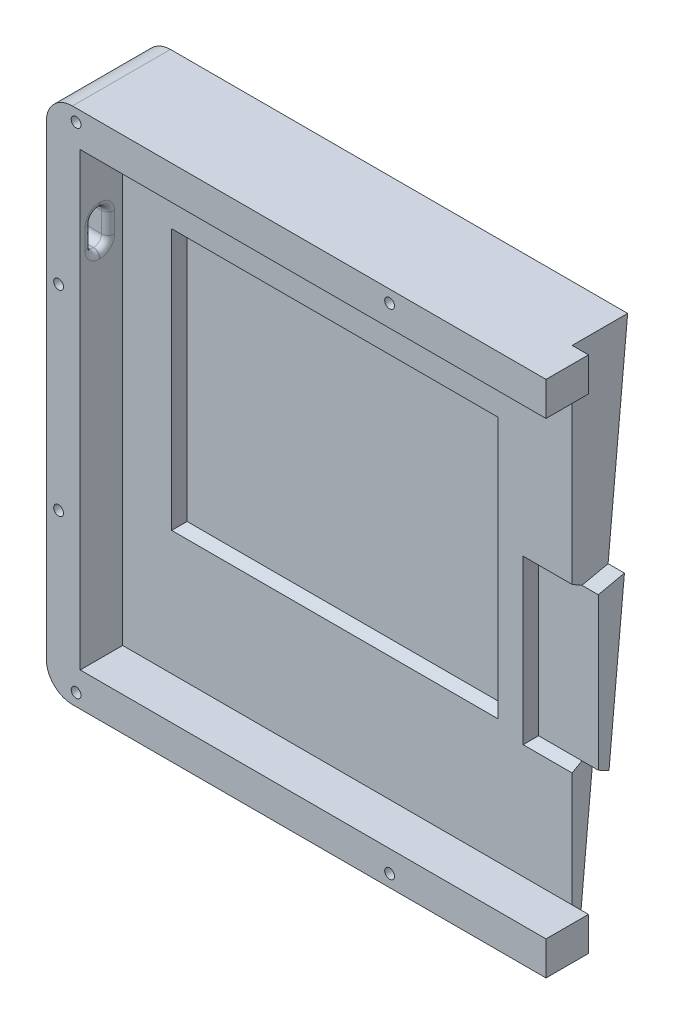
SolidWorks part; units mm, degrees
ref_plane "Front Plane" through (0, 0, 0) normal (0, 0, 1) x (1, 0, 0)
ref_plane "Top Plane" through (0, 0, 0) normal (0, 1, 0) x (1, 0, 0)
ref_plane "Right Plane" through (0, 0, 0) normal (1, 0, 0) x (0, 0, -1)
sketch "Model" plane through (0, 0, 0) normal (0, 0, 1) x (1, 0, 0)
  line L0 (0, 11) -> (0, 150.75)
  line L1 (306.2071, 11.0112) -> (306.0112, 150.7612)
  line L2 (298.0112, 158.75) -> (8, 158.75)
  line L3 (0, 11) -> (0, 8)
  line L4 (8, 0) -> (298.2071, 0)
  line L5 (306.2071, 11.0112) -> (306.2071, 8)
  line L6 (295.63, 10.37) -> (10.37, 10.37)
  line L7 (10.37, 10.37) -> (10.37, 148.38)
  line L8 (10.37, 148.38) -> (295.63, 148.38)
  line L9 (295.63, 148.38) -> (295.63, 10.37)
  arc A0 (8, 158.75) -> (0, 150.75) centre (8, 150.75) ccw
  arc A1 (306.0112, 150.7612) -> (298.0112, 158.75) centre (298.0112, 150.75) ccw
  arc A2 (0, 8) -> (8, 0) centre (8, 8) ccw
  arc A3 (298.2071, 0) -> (306.2071, 8) centre (298.2071, 8) ccw
  circle A4 centre (105.1086, 3.75) radius 1.5
  circle A5 centre (9.1086, 3.75) radius 1.5
  circle A6 centre (201.1085, 3.8173) radius 1.5
  circle A7 centre (297.1084, 3.9518) radius 1.5
  circle A8 centre (105.1086, 155) radius 1.5
  circle A9 centre (9.1086, 155) radius 1.5
  circle A10 centre (201.1085, 154.9327) radius 1.5
  circle A11 centre (297.1084, 154.7982) radius 1.5
  circle A12 centre (3.75, 109.375) radius 1.5
  circle A13 centre (3.75, 49.375) radius 1.5
  circle A14 centre (302.3189, 109.5842) radius 1.5
  circle A15 centre (302.403, 49.5843) radius 1.5
sketch "草图2" plane through (0, 0, 0) normal (0, 0, 1) x (1, 0, 0)
  line L0 (0, 11) -> (0, 150.75)
  line L1 (306.2071, 11.0112) -> (306.0112, 150.7612)
  line L2 (298.0112, 158.75) -> (8, 158.75)
  line L3 (0, 11) -> (0, 8)
  line L4 (8, 0) -> (298.2071, 0)
  line L5 (306.2071, 11.0112) -> (306.2071, 8)
  line L6 (295.63, 10.37) -> (10.37, 10.37)
  line L7 (10.37, 10.37) -> (10.37, 148.38)
  line L8 (10.37, 148.38) -> (295.63, 148.38)
  line L9 (295.63, 148.38) -> (295.63, 10.37)
  arc A0 (8, 158.75) -> (0, 150.75) centre (8, 150.75) ccw
  arc A1 (306.0112, 150.7612) -> (298.0112, 158.75) centre (298.0112, 150.75) ccw
  arc A2 (0, 8) -> (8, 0) centre (8, 8) ccw
  arc A3 (298.2071, 0) -> (306.2071, 8) centre (298.2071, 8) ccw
  circle A4 centre (105.1086, 3.75) radius 1.5
  circle A5 centre (9.1086, 3.75) radius 1.5
  circle A6 centre (201.1085, 3.8173) radius 1.5
  circle A7 centre (297.1084, 3.9518) radius 1.5
  circle A8 centre (105.1086, 155) radius 1.5
  circle A9 centre (9.1086, 155) radius 1.5
  circle A10 centre (201.1085, 154.9327) radius 1.5
  circle A11 centre (297.1084, 154.7982) radius 1.5
  circle A12 centre (3.75, 109.375) radius 1.5
  circle A13 centre (3.75, 49.375) radius 1.5
  circle A14 centre (302.3189, 109.5842) radius 1.5
  circle A15 centre (302.403, 49.5843) radius 1.5
sketch "草图3" plane through (0, 0, 0) normal (0, 0, 1) x (1, 0, 0)
  line L0 (0, 11) -> (0, 150.75)
  line L1 (306.2071, 11.0112) -> (306.0112, 150.7612)
  line L2 (298.0112, 158.75) -> (8, 158.75)
  line L3 (0, 11) -> (0, 8)
  line L4 (8, 0) -> (298.2071, 0)
  line L5 (306.2071, 11.0112) -> (306.2071, 8)
  line L6 (295.63, 10.37) -> (10.37, 10.37)
  line L7 (10.37, 10.37) -> (10.37, 148.38)
  line L8 (10.37, 148.38) -> (295.63, 148.38)
  line L9 (295.63, 148.38) -> (295.63, 10.37)
  arc A0 (8, 158.75) -> (0, 150.75) centre (8, 150.75) ccw
  arc A1 (306.0112, 150.7612) -> (298.0112, 158.75) centre (298.0112, 150.75) ccw
  arc A2 (0, 8) -> (8, 0) centre (8, 8) ccw
  arc A3 (298.2071, 0) -> (306.2071, 8) centre (298.2071, 8) ccw
  circle A4 centre (105.1086, 3.75) radius 1.5
  circle A5 centre (9.1086, 3.75) radius 1.5
  circle A6 centre (201.1085, 3.8173) radius 1.5
  circle A7 centre (297.1084, 3.9518) radius 1.5
  circle A8 centre (105.1086, 155) radius 1.5
  circle A9 centre (9.1086, 155) radius 1.5
  circle A10 centre (201.1085, 154.9327) radius 1.5
  circle A11 centre (297.1084, 154.7982) radius 1.5
  circle A12 centre (3.75, 109.375) radius 1.5
  circle A13 centre (3.75, 49.375) radius 1.5
  circle A14 centre (302.3189, 109.5842) radius 1.5
  circle A15 centre (302.403, 49.5843) radius 1.5
sketch "草图4" plane through (0, 0, 0) normal (0, 0, 1) x (1, 0, 0)
  line L0 (0, 11) -> (0, 150.75)
  line L1 (306.2071, 11.0112) -> (306.0112, 150.7612)
  line L2 (298.0112, 158.75) -> (8, 158.75)
  line L3 (0, 11) -> (0, 8)
  line L4 (8, 0) -> (298.2071, 0)
  line L5 (306.2071, 11.0112) -> (306.2071, 8)
  line L6 (295.63, 10.37) -> (10.37, 10.37)
  line L7 (10.37, 10.37) -> (10.37, 148.38)
  line L8 (10.37, 148.38) -> (295.63, 148.38)
  line L9 (295.63, 148.38) -> (295.63, 10.37)
  arc A0 (8, 158.75) -> (0, 150.75) centre (8, 150.75) ccw
  arc A1 (306.0112, 150.7612) -> (298.0112, 158.75) centre (298.0112, 150.75) ccw
  arc A2 (0, 8) -> (8, 0) centre (8, 8) ccw
  arc A3 (298.2071, 0) -> (306.2071, 8) centre (298.2071, 8) ccw
  circle A4 centre (105.1086, 3.75) radius 1.5
  circle A5 centre (9.1086, 3.75) radius 1.5
  circle A6 centre (201.1085, 3.8173) radius 1.5
  circle A7 centre (297.1084, 3.9518) radius 1.5
  circle A8 centre (105.1086, 155) radius 1.5
  circle A9 centre (9.1086, 155) radius 1.5
  circle A10 centre (201.1085, 154.9327) radius 1.5
  circle A11 centre (297.1084, 154.7982) radius 1.5
  circle A12 centre (3.75, 109.375) radius 1.5
  circle A13 centre (3.75, 49.375) radius 1.5
  circle A14 centre (302.3189, 109.5842) radius 1.5
  circle A15 centre (302.403, 49.5843) radius 1.5
extrude "凸台-拉伸1" add sketch "Model" against normal blind 30 contours L2 A0 L0 L3 A2 L4 A3 L5 L1 A1
extrude "切除-拉伸1" cut sketch "草图2" against normal blind 5 contours A4 | A5 | A10 | A11 | A7 | A6 | A13 | A12 | A8 | A9 | A14 | A15
sketch "草图6" plane through (0, 0, 0) normal (-1, 0, 0) x (0, 0, 1)
  line L0 (-30, 158.75) -> (-30, 0)
  line L1 (-30, 0) -> (-15, 0)
  line L2 (-30, 0) -> (0, 0) construction
  line L3 (-15, 0) -> (-30, 158.75)
extrude "切除-拉伸4" cut sketch "草图6" against normal blind 307 contours L3 L0 L1
extrude "切除-拉伸5" cut sketch "草图3" against normal blind 13 contours L8 L9 L6 L7
sketch "草图8" plane through (0, 0, 0) normal (0, 0, 1) x (1, 0, 0)
  line L0 (10.37, 148.38) -> (10.37, 129.38)
  line L1 (10.37, 10.37) -> (10.37, 148.38) construction
  line L2 (10.37, 129.38) -> (0, 129.38)
  line L3 (0, 11) -> (0, 150.75) construction
  line L4 (0, 129.38) -> (0, 118.38)
  line L5 (0, 118.38) -> (10.37, 118.38)
  line L6 (295.63, 10.37) -> (232.13, 10.37)
  line L7 (295.63, 10.37) -> (10.37, 10.37) construction
  line L8 (232.13, 10.37) -> (232.13, 0)
  line L9 (8, 0) -> (298.2071, 0) construction
  line L10 (232.13, 0) -> (220.13, 0)
  line L11 (220.13, 0) -> (220.13, 10.37)
  line L12 (220.13, 10.37) -> (232.13, 10.37)
  line L13 (10.37, 118.38) -> (10.37, 129.38)
sketch "草图9" plane through (0, 0, -13) normal (0, 0, 1) x (1, 0, 0)
  line L5 (25.37, 128.38) -> (125.37, 128.38)
  line L6 (25.37, 128.38) -> (25.37, 48.38)
  line L7 (25.37, 48.38) -> (125.37, 48.38)
  line L8 (125.37, 128.38) -> (125.37, 48.38)
sketch "草图12" plane through (0, 0, -13) normal (0, 0, 1) x (1, 0, 0)
  line L11 (133, 45.37) -> (173, 45.37)
  line L12 (133, 45.37) -> (133, 95.37)
  line L13 (133, 95.37) -> (173, 95.37)
  line L14 (173, 45.37) -> (173, 95.37)
extrude "切除-拉伸7" cut sketch "草图12" against normal blind 3 draft 30
extrude "切除-拉伸8" cut sketch "草图9" against normal blind 3 draft 30 contours L5 L8 L7 L6
sketch "草图14" plane through (0, 0, 0) normal (-1, 0, 0) x (0, 0, 1)
  line L6 (-5.9, 129.38) -> (-6.1, 129.38)
  line L7 (-3.5, 126.98) -> (-3.5, 120.78)
  line L8 (-5.9, 118.38) -> (-6.1, 118.38)
  line L9 (-8.5, 126.98) -> (-8.5, 120.78)
  arc A0 (-6.1, 118.38) -> (-8.5, 120.78) centre (-6.1, 120.78) cw
  arc A1 (-5.9, 118.38) -> (-3.5, 120.78) centre (-5.9, 120.78) ccw
  arc A2 (-3.5, 126.98) -> (-5.9, 129.38) centre (-5.9, 126.98) ccw
  arc A3 (-8.5, 126.98) -> (-6.1, 129.38) centre (-6.1, 126.98) cw
  dimension "D1" = 2.4
extrude "切除-拉伸9" cut sketch "草图14" against normal blind 11 contours L7 A1 L8 A0 L9 A3 L6 A2
fillet "圆角1" radius 2 8 edges at (0, 128.6771, -7.7971) (0, 129.38, -6) (0, 128.6771, -4.2029) (0, 123.88, -3.5) (0, 119.0829, -4.2029) (0, 118.38, -6) (0, 119.0829, -7.7971) (0, 123.88, -8.5)
sketch "草图15" plane through (0, 0, 0) normal (0, -1, 0) x (1, 0, 0)
  line L6 (222.53, -3.9597) -> (229.73, -3.9597)
  line L7 (220.13, -6.3597) -> (220.13, -6.5597)
  line L8 (222.53, -8.9597) -> (229.73, -8.9597)
  line L9 (232.13, -6.3597) -> (232.13, -6.5597)
  arc A0 (220.13, -6.5597) -> (222.53, -8.9597) centre (222.53, -6.5597) ccw
  arc A1 (232.13, -6.5597) -> (229.73, -8.9597) centre (229.73, -6.5597) cw
  arc A2 (232.13, -6.3597) -> (229.73, -3.9597) centre (229.73, -6.3597) ccw
  arc A3 (222.53, -3.9597) -> (220.13, -6.3597) centre (222.53, -6.3597) ccw
  dimension "D1" = 2.4
extrude "切除-拉伸10" cut sketch "草图15" against normal blind 11 contours L6 A2 L9 A1 L8 A0 L7 A3
fillet "圆角2" radius 2 8 edges at (232.13, 0, -6.4597) (231.4271, 0, -4.6626) (226.13, 0, -3.9597) (220.8329, 0, -4.6626) (220.13, 0, -6.4597) (220.8329, 0, -8.2567) (226.13, 0, -8.9597) (231.4271, 0, -8.2567)
fillet "圆角3" radius 2 8 edges at (10.37, 129.38, -6) (10.37, 128.6771, -4.2029) (10.37, 123.88, -3.5) (10.37, 119.0829, -4.2029) (10.37, 118.38, -6) (10.37, 119.0829, -7.7971) (10.37, 123.88, -8.5) (10.37, 128.6771, -7.7971)
fillet "圆角4" radius 2 8 edges at (231.4271, 10.37, -8.2567) (232.13, 10.37, -6.4597) (231.4271, 10.37, -4.6626) (226.13, 10.37, -3.9597) (220.8329, 10.37, -4.6626) (220.13, 10.37, -6.4597) (220.8329, 10.37, -8.2567) (226.13, 10.37, -8.9597)
sketch "草图17" plane through (0, 158.75, 0) normal (0, 1, 0) x (1, 0, 0)
  line L0 (153.0056, 30) -> (153.0056, 0)
  line L1 (298.0112, 30) -> (8, 30) construction
  line L2 (298.0112, 0) -> (8, 0) construction
sketch "草图18" plane through (0, 0, 0) normal (0, -1, 0) x (1, 0, 0)
  line L0 (153.0056, 0) -> (153.0056, -15)
  line L1 (153.0056, -30) -> (153.0056, 0) construction
ref_plane "基准面1" through (153.0056, 0, 0) normal (1, 0, 0) x (0, 0, -1)
split "分割1" trim tools "基准面1" bodies to split 111 resulting bodies 112 113
delete or keep bodies "实体-删除/保留 2" type delete bodies bodies 112
sketch "草图19" plane through (153.0056, 0, 0) normal (1, 0, 0) x (0, 0, -1)
  line L2 (13, 148.38) -> (13, 95.37)
  line L4 (15, 0) -> (30, 158.75) construction
  line L5 (24.0113, 95.37) -> (30, 158.75)
  line L8 (19.2869, 45.37) -> (15, 0)
  line L9 (13, 45.37) -> (13, 0)
  line L10 (15, 0) -> (0, 0) construction
  line L11 (13, 0) -> (15, 0)
  line L12 (13, 95.37) -> (16, 93.6379)
  line L13 (16, 93.6379) -> (24.0113, 95.37)
  line L14 (13, 45.37) -> (16, 47.1021)
  line L15 (16, 47.1021) -> (19.2869, 45.37)
  line L16 (13, 148.38) -> (13, 158.75)
  line L17 (0, 158.75) -> (30, 158.75) construction
  line L18 (13, 158.75) -> (30, 158.75)
extrude "切除-拉伸11" cut sketch "草图19" against normal blind 5
